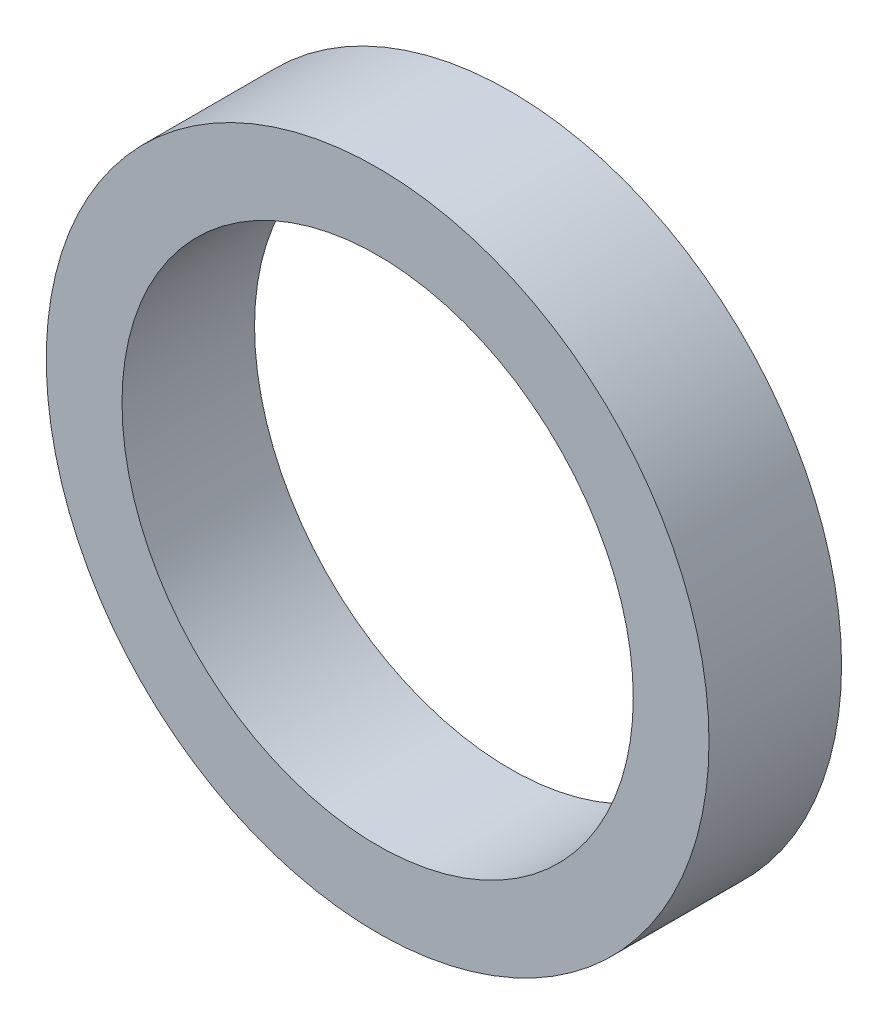
SolidWorks part; units mm, degrees
ref_plane "正面" through (0, 0, 0) normal (0, 0, 1) x (1, 0, 0)
ref_plane "平面" through (0, 0, 0) normal (0, 1, 0) x (1, 0, 0)
ref_plane "右側面" through (0, 0, 0) normal (1, 0, 0) x (0, 0, -1)
sketch "ｽｹｯﾁ1" plane through (0, 0, 0) normal (0, 0, 1) x (1, 0, 0)
  circle A0 centre (0, 0) radius 5.4
  circle A1 centre (0, 0) radius 7
  dimension "D1" = 10.8
  dimension "D2" = 14
extrude "ﾎﾞｽ - 押し出し1" add sketch "ｽｹｯﾁ1" along normal mid plane 2.8
